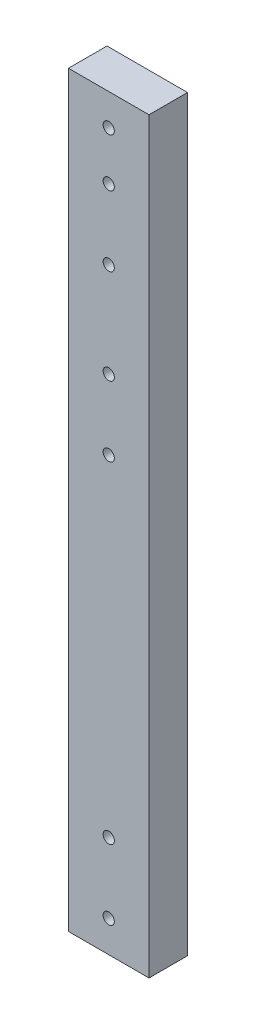
SolidWorks part; units mm, degrees
ref_plane "正面" through (0, 0, 0) normal (0, 0, 1) x (1, 0, 0)
ref_plane "平面" through (0, 0, 0) normal (0, 1, 0) x (1, 0, 0)
ref_plane "右側面" through (0, 0, 0) normal (1, 0, 0) x (0, 0, -1)
sketch "ｽｹｯﾁ1" plane through (0, 0, 5) normal (0, 0, 1) x (1, 0, 0)
  line L0 (11.5, 99.5) -> (-11.5, 99.5)
  line L1 (-11.5, 99.5) -> (-11.5, -114)
  line L2 (-11.5, -114) -> (11.5, -114)
  line L3 (11.5, -114) -> (11.5, 99.5)
  line L4 (7.5, 95.5) -> (-7.5, 95.5)
  line L5 (-7.5, 95.5) -> (-7.5, -110)
  line L6 (-7.5, -110) -> (7.5, -110)
  line L7 (7.5, -110) -> (7.5, 95.5)
  line L8 (7.5, 95.5) -> (-7.5, 95.5) construction
  line L9 (-7.5, 95.5) -> (-7.5, -110) construction
  line L10 (-7.5, -110) -> (7.5, -110) construction
  line L11 (7.5, -110) -> (7.5, 95.5) construction
  circle A1 centre (0, -105) radius 1.6
  circle A2 centre (0, -105) radius 1.6
  circle A3 centre (0, -85) radius 1.6
  circle A4 centre (0, -85) radius 1.6
  circle A5 centre (0, 90.5) radius 1.6
  circle A6 centre (0, 90.5) radius 1.6
  circle A7 centre (0, 76.66) radius 1.6
  circle A8 centre (0, 76.66) radius 1.6
  circle A9 centre (0, 56.66) radius 1.6
  circle A10 centre (0, 56.66) radius 1.6
  circle A11 centre (0, 29.6) radius 1.6
  circle A12 centre (0, 29.6) radius 1.6
  circle A13 centre (0, 9.6) radius 1.6
  circle A14 centre (0, 9.6) radius 1.6
  dimension "D1" = 0
  dimension "D2" = 0
  dimension "D3" = 0
  dimension "D4" = 0
  dimension "D5" = 0
  dimension "D6" = 0
  dimension "D7" = 0
  dimension "D8" = 0
  dimension "D9" = 4
extrude "ﾎﾞｽ - 押し出し1" add sketch "ｽｹｯﾁ1" along normal blind 4
sketch "ｽｹｯﾁ2" plane through (0, 0, 5) normal (0, 0, -1) x (-1, 0, 0)
  line L0 (7.65, -110.15) -> (7.65, 95.65)
  line L1 (7.65, 95.65) -> (-7.65, 95.65)
  line L2 (-7.65, 95.65) -> (-7.65, -110.15)
  line L3 (-7.65, -110.15) -> (7.65, -110.15)
  line L4 (-11.5, 99.5) -> (-11.5, -114)
  line L5 (-11.5, -114) -> (11.5, -114)
  line L6 (11.5, -114) -> (11.5, 99.5)
  line L7 (11.5, 99.5) -> (-11.5, 99.5)
  line L8 (-11.5, 99.5) -> (-11.5, -114)
  line L9 (-11.5, -114) -> (11.5, -114)
  line L10 (11.5, -114) -> (11.5, 99.5)
  line L11 (11.5, 99.5) -> (-11.5, 99.5)
  line L12 (7.5, 95.5) -> (-7.5, 95.5)
  line L13 (-7.5, 95.5) -> (-7.5, -110)
  line L14 (-7.5, -110) -> (7.5, -110)
  line L15 (7.5, -110) -> (7.5, 95.5)
  line L16 (7.5, 95.5) -> (-7.5, 95.5) construction
  line L17 (-7.5, 95.5) -> (-7.5, -110) construction
  line L18 (-7.5, -110) -> (7.5, -110) construction
  line L19 (7.5, -110) -> (7.5, 95.5) construction
  dimension "D1" = 0
  dimension "D2" = 0
  dimension "D3" = 0.15
extrude "ﾎﾞｽ - 押し出し2" add sketch "ｽｹｯﾁ2" along normal blind 7
chamfer "面取り1" distance 2 angle 45 4 edges at (0, -110.15, -2) (-7.65, -7.25, -2) (0, 95.65, -2) (7.65, -7.25, -2)
